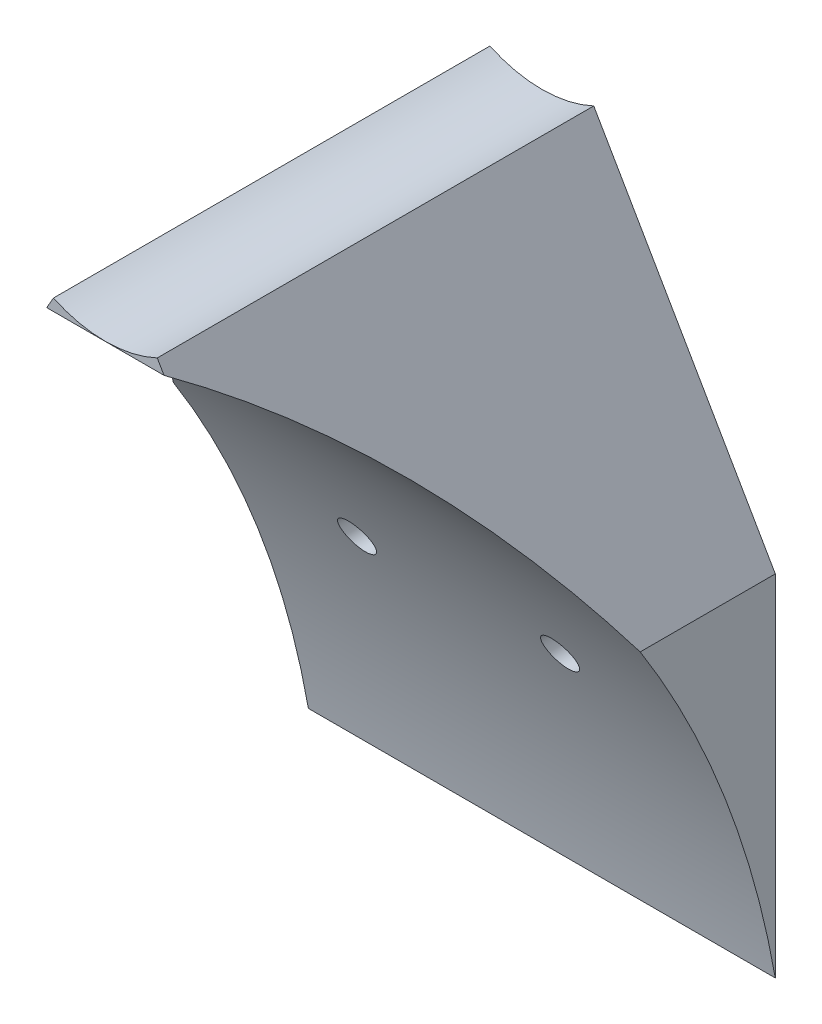
SolidWorks part; units mm, degrees
ref_plane "Front Plane" through (0, 0, 0) normal (0, 0, 1) x (1, 0, 0)
ref_plane "Top Plane" through (0, 0, 0) normal (0, 1, 0) x (1, 0, 0)
ref_plane "Right Plane" through (0, 0, 0) normal (1, 0, 0) x (0, 0, -1)
sketch "Sketch1" plane through (0, 0, 0) normal (0, 0, 1) x (1, 0, 0)
  line L0 (0, 0) -> (0, -127) construction
  line L1 (0, 0) -> (38.1, -65.9911) construction
  line L2 (0, 0) -> (-38.1, -65.9911) construction
  line L3 (-38.1, -65.9911) -> (-38.1, -121.1503) construction
  line L5 (0, 0) -> (0, -127) construction
  line L6 (38.1, -121.1503) -> (38.1, -65.9911) construction
  line L7 (38.1, -121.1503) -> (38.1, -159.2503) construction
  line L8 (-50.8, -197.3503) -> (0, -197.3503) construction
  line L9 (-50.8, -195.7628) -> (0, -195.7628) construction
  line L10 (36.5125, -121.1503) -> (36.5125, -159.2503) construction
  line L11 (36.5125, -121.1503) -> (36.5125, -66.4165)
  line L12 (0, -3.175) -> (36.5125, -66.4165)
  line L13 (0, -3.175) -> (-36.5125, -66.4165)
  line L14 (-36.5125, -66.4165) -> (-36.5125, -121.1503)
  line L15 (-36.5125, -121.1503) -> (-38.1, -121.1503) construction
  line L16 (-50.8, -195.7628) -> (-50.8, -197.3503) construction
  line L17 (36.5125, -121.1503) -> (-36.5125, -121.1503)
  circle A0 centre (0, 0) radius 127 construction
  circle A1 centre (0, 0) radius 76.2 construction
  arc A2 (38.1, -159.2503) -> (0, -197.3503) centre (0, -159.2503) cw construction
  arc A3 (36.5125, -159.2503) -> (0, -195.7628) centre (0, -159.2503) cw construction
  point P2 (-15.875, -74.528)
  point P12 (0, 0)
  point P14 (15.875, -74.528)
  point P25 (0, -38.1)
  dimension "D2" = 152.4
  dimension "D6" = 1.5875
  dimension "D1" = 127
  dimension "D3" = 38.1
  dimension "D4" = 50.8
  dimension "D5" = 60
  dimension "D7" = 38.1
  dimension "D8" = 31.75
extrude "Boss-Extrude1" add sketch "Sketch1" along normal blind 76.2
sketch "Sketch2" plane through (0, 0, 0) normal (1, 0, 0) x (0, 0, -1)
  line L3 (-76.2, -121.1503) -> (0, -121.1503) construction
  line L4 (-76.2, -121.1503) -> (-76.2, -66.4165) construction
  line L6 (-76.2, -121.1503) -> (0, -121.1503)
  line L7 (-76.2, -121.1503) -> (-76.2, -66.4165)
  line L10 (-76.2, -66.4165) -> (-76.2, -3.175) construction
  line L11 (-76.2, -22.225) -> (-76.2, -66.4165)
  line L12 (0, -66.4165) -> (0, -3.175) construction
  line L13 (-76.2, -3.175) -> (0, -3.175) construction
  line L14 (-68.2625, -19.0675) -> (-68.2625, -3.175)
  line L15 (-68.2625, -3.175) -> (-76.2, -3.175)
  line L16 (-76.2, -3.175) -> (-76.2, -22.225)
  arc A0 (-68.2625, -19.0675) -> (0, -121.1503) centre (-150.0796, -147.6432) cw
  dimension "D1" = 68.2625
  dimension "D2" = 152.4
extrude "Cut-Extrude1" cut sketch "Sketch2" along normal up to surface (73.025 mm away) from surface at -36.5125 up to face at (36.5125, -93.7834, 38.1) starting at face at (-36.5125, -93.7834, 38.1)
sketch "Sketch5" plane through (0, 0, 0) normal (0, 0, 1) x (1, 0, 0)
  line L0 (0, -82.55) -> (0, 0) construction
  circle A0 centre (0, 0) radius 82.55 construction
  point P0 (0, -38.1)
  point P4 (-15.875, -81.0092)
  point P5 (15.875, -81.0092)
  dimension "D1" = 38.1
  dimension "D3" = 165.1
  dimension "D2" = 31.75
hole_wizard "M5 Clearance Hole1" positions "Sketch7" profile "Sketch8" hole size "M5" standard "ANSI Metric" end condition through all
sketch "Sketch7" plane through (0, 0, 0) normal (0, 0, -1) x (-1, 0, 0)
  point P0 (-15.875, -81.0092)
  point P3 (15.875, -81.0092)
  point P6 (0, -38.1)
sketch "Sketch8" plane through (15.875, -81.0092, 0) normal (1, 0, 0) x (0, 1, 0)
  line L0 (0, 0) -> (0, 68.2625)
  line L1 (0, 68.2625) -> (2.75, 68.2625)
  line L2 (2.75, 68.2625) -> (2.75, 0)
  line L5 (2.75, 0) -> (0, 0)
  line L11 (0, -6.35) -> (0, 107.95) construction
  dimension "Thru Hole Dia." = 5.5
  dimension "Thru Hole Depth" = 68.2625
sketch "Sketch10" plane through (0, 0, 0) normal (0, 0, -1) x (-1, 0, 0)
  circle A0 centre (0, 0) radius 19.05
  dimension "D1" = 38.1
extrude "Cut-Extrude2" cut sketch "Sketch10" against normal up to next
